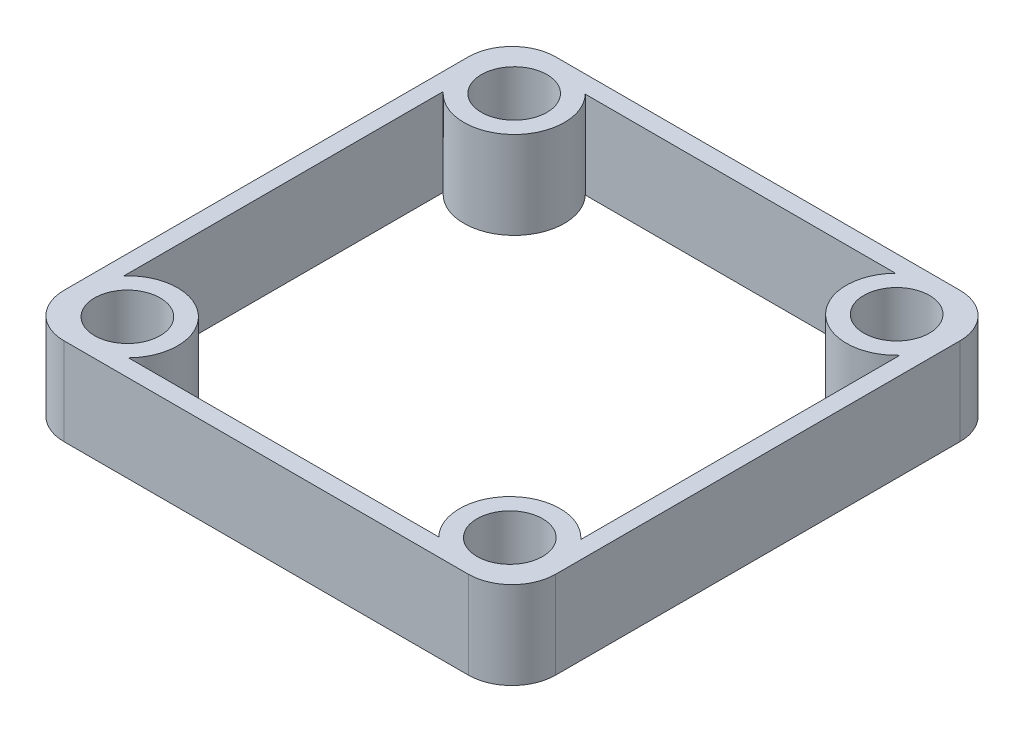
SolidWorks part; units mm, degrees
ref_plane "Front Plane" through (0, 0, 0) normal (0, 0, 1) x (1, 0, 0)
ref_plane "Top Plane" through (0, 0, 0) normal (0, 1, 0) x (1, 0, 0)
ref_plane "Right Plane" through (0, 0, 0) normal (1, 0, 0) x (0, 0, -1)
sketch "Sketch1" plane through (0, 0, 0) normal (0, 1, 0) x (1, 0, 0)
  line L0 (0, 11.25) -> (0, -11.25) construction
  line L1 (-9.25, 11.25) -> (9.25, 11.25)
  line L2 (-11.25, 9.25) -> (-11.25, -9.25)
  line L3 (-9.25, -11.25) -> (9.25, -11.25)
  line L4 (11.25, 9.25) -> (11.25, -9.25)
  line L5 (-11.25, 11.25) -> (11.25, -11.25) construction
  line L6 (-11.25, -11.25) -> (11.25, 11.25) construction
  line L7 (11.25, 0) -> (-11.2452, 0) construction
  line L8 (-7.0977, 10.45) -> (7.0977, 10.45)
  line L9 (10.45, 7.3008) -> (10.45, -7.3008)
  line L10 (-7.0977, -10.45) -> (7.0977, -10.45)
  line L11 (-10.45, 7.3008) -> (-10.45, -7.3008)
  line L12 (10.45, 9.25) -> (10.45, -9.25) construction
  line L13 (-9.25, -10.45) -> (9.25, -10.45) construction
  line L14 (-10.45, 9.25) -> (-10.45, -9.25) construction
  line L15 (-9.25, 10.45) -> (9.25, 10.45) construction
  arc A0 (9.25, 11.25) -> (11.25, 9.25) centre (9.25, 9.25) cw
  arc A1 (9.25, -11.25) -> (11.25, -9.25) centre (9.25, -9.25) ccw
  arc A2 (-11.25, -9.25) -> (-9.25, -11.25) centre (-9.25, -9.25) ccw
  arc A3 (-9.25, 11.25) -> (-11.25, 9.25) centre (-9.25, 9.25) ccw
  circle A4 centre (8.75, 8.85) radius 1.5
  circle A5 centre (8.75, -8.85) radius 1.5
  circle A6 centre (-8.75, 8.85) radius 1.5
  circle A7 centre (-8.75, -8.85) radius 1.5
  arc A8 (7.0977, 10.45) -> (10.45, 7.3008) centre (8.75, 8.85) ccw
  arc A9 (-7.0977, 10.45) -> (-10.45, 7.3008) centre (-8.75, 8.85) cw
  arc A10 (7.0977, -10.45) -> (10.45, -7.3008) centre (8.75, -8.85) cw
  arc A11 (-7.0977, -10.45) -> (-10.45, -7.3008) centre (-8.75, -8.85) ccw
  arc A16 (9.25, -10.45) -> (10.45, -9.25) centre (9.25, -9.25) ccw construction
  circle A17 centre (8.75, -8.85) radius 2.3 construction
  circle A18 centre (-8.75, -8.85) radius 2.3 construction
  arc A19 (-10.45, -9.25) -> (-9.25, -10.45) centre (-9.25, -9.25) ccw construction
  circle A20 centre (8.75, 8.85) radius 2.3 construction
  arc A21 (9.25, 10.45) -> (10.45, 9.25) centre (9.25, 9.25) cw construction
  circle A22 centre (-8.75, 8.85) radius 2.3 construction
  arc A23 (-9.25, 10.45) -> (-10.45, 9.25) centre (-9.25, 9.25) ccw construction
  point P0 (0, 0)
  point P58 (-7.1752, 7.1737)
  dimension "D3" = 2
  dimension "D4" = 2
  dimension "D5" = 3
  dimension "D1" = 22.5
  dimension "D2" = 22.5
  dimension "D6" = 2.5
  dimension "D7" = 2.4
  dimension "D8" = 8.85
  dimension "D11" = 2.3
  dimension "D9" = 0.8
  dimension "D10" = 0.8
extrude "Boss-Extrude1" add sketch "Sketch1" along normal blind 4
